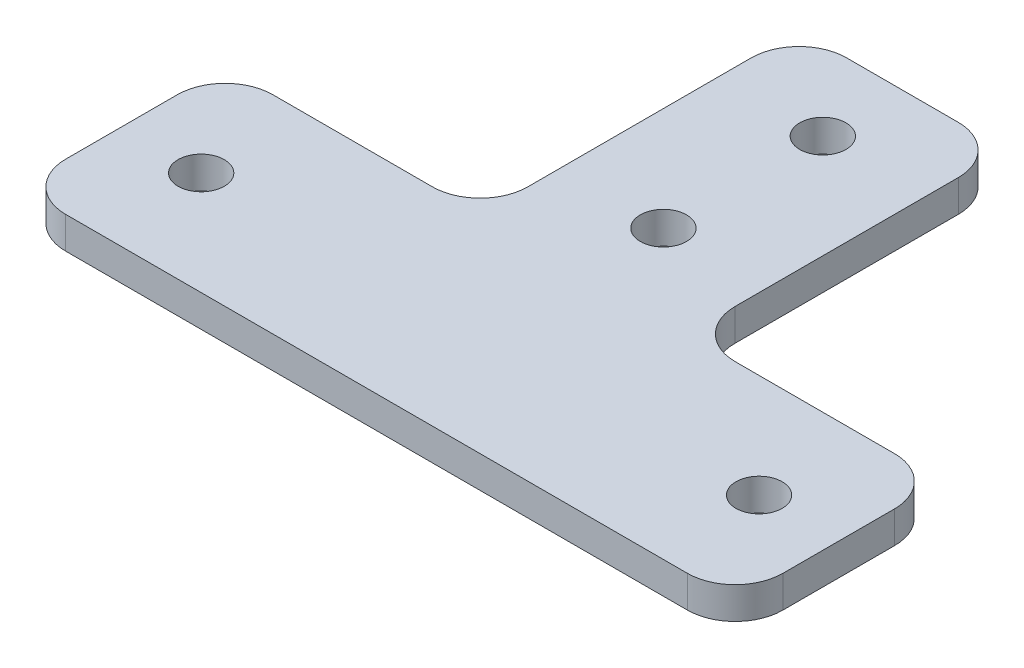
SolidWorks part; units mm, degrees
material "Thornel Mat VMA"
ref_plane "前视基准面" through (0, 0, 0) normal (0, 0, 1) x (1, 0, 0)
ref_plane "上视基准面" through (0, 0, 0) normal (0, 1, 0) x (1, 0, 0)
ref_plane "右视基准面" through (0, 0, 0) normal (1, 0, 0) x (0, 0, -1)
other "Configuration Table"
sketch "草图1" plane through (0, 0, 0) normal (0, 1, 0) x (1, 0, 0)
  line L0 (-43.0981, 0) -> (49.5574, 0) construction
  line L1 (-22.5, -6.5) -> (22.5, -6.5) construction
  line L2 (-22.5, -6.5) -> (-22.5, 6.5) construction
  line L3 (-22.5, 6.5) -> (22.5, 6.5) construction
  line L4 (22.5, -6.5) -> (22.5, 6.5) construction
  line L5 (-22.5, -6.5) -> (22.5, 6.5) construction
  line L6 (-22.5, 6.5) -> (22.5, -6.5) construction
  line L7 (-6.5, -6.5) -> (6.5, -6.5) construction
  line L8 (-6.5, -6.5) -> (-6.5, 26.5) construction
  line L9 (-6.5, 26.5) -> (6.5, 26.5) construction
  line L10 (6.5, -6.5) -> (6.5, 26.5) construction
  line L11 (0, 51.3517) -> (0, -26.5191) construction
  line L12 (-22.5, 6.5) -> (-22.5, -6.5)
  line L13 (-22.5, -6.5) -> (22.5, -6.5)
  line L14 (22.5, -6.5) -> (22.5, 6.5)
  line L15 (22.5, 6.5) -> (6.5, 6.5)
  line L16 (6.5, 6.5) -> (6.5, 26.5)
  line L17 (6.5, 26.5) -> (-6.5, 26.5)
  line L18 (-6.5, 26.5) -> (-6.5, 6.5)
  line L19 (-6.5, 6.5) -> (-22.5, 6.5)
  circle A0 centre (-17.5, 0) radius 1.45
  circle A1 centre (17.5, 0) radius 1.45
  circle A2 centre (0, 11.5) radius 1.45
  circle A3 centre (0, 21.5) radius 1.45
  point P0 (0, 0)
  dimension "D3" = 2.9
  dimension "D5" = 17.5
  dimension "D6" = 5
  dimension "D8" = 10
  dimension "D1" = 13
  dimension "D2" = 13
  dimension "D4" = 17.5
  dimension "D7" = 5
  dimension "D9" = 5
extrude "凸台-拉伸1" add sketch "草图1" along normal blind 2
fillet "圆角1" radius 3 8 edges at (22.5, 1, -6.5) (22.5, 1, 6.5) (-22.5, 1, 6.5) (-22.5, 1, -6.5) (-6.5, 1, -6.5) (-6.5, 1, -26.5) (6.5, 1, -26.5) (6.5, 1, -6.5)
